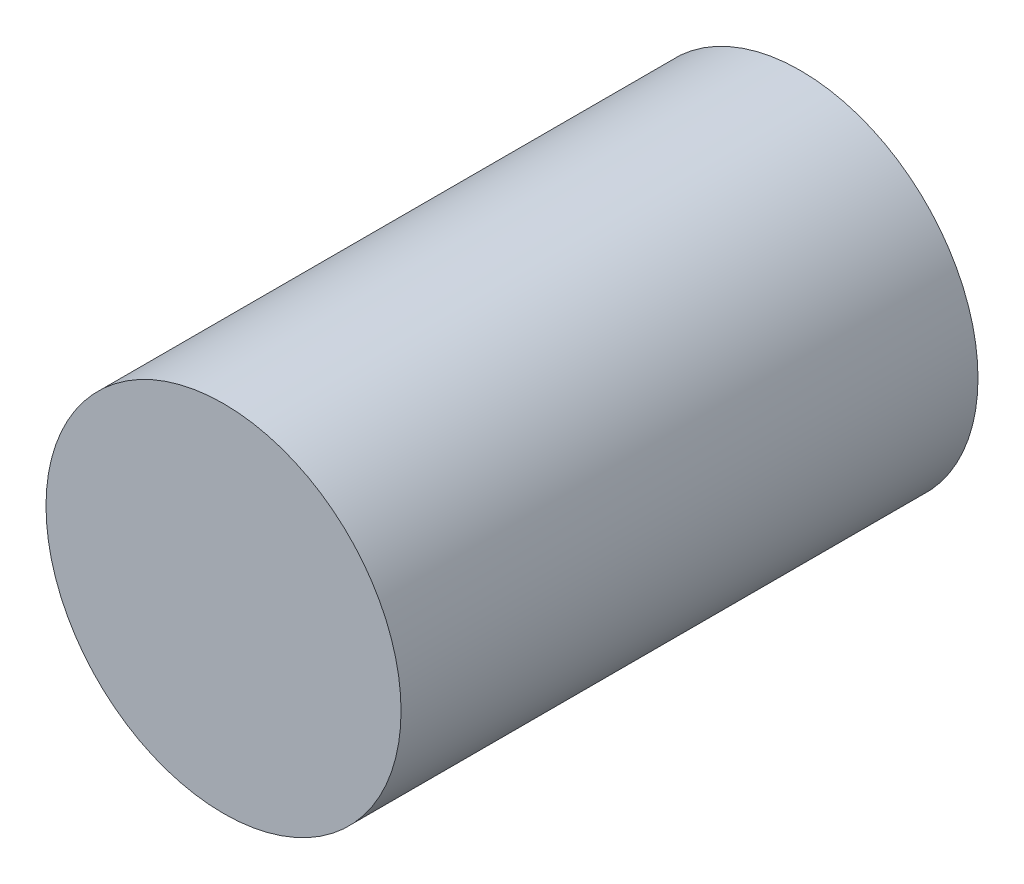
SolidWorks part; units mm, degrees
ref_plane "Front Plane" through (0, 0, 0) normal (0, 0, 1) x (1, 0, 0)
ref_plane "Top Plane" through (0, 0, 0) normal (0, 1, 0) x (1, 0, 0)
ref_plane "Right Plane" through (0, 0, 0) normal (1, 0, 0) x (0, 0, -1)
sketch "Sketch1" plane through (0, 0, 0) normal (0, 0, 1) x (1, 0, 0)
  circle A0 centre (4, 4) radius 4
  dimension "D1" = 8
extrude "Profile" add sketch "Sketch1" along normal blind 13
equation "\"Profile_Depth\"= 13mm"
equation "\"D1@Profile\" = \"Profile_Depth\""
equation "\"Profile_Sketch_1\"= 8mm"
equation "\"D1@Sketch1\" = \"Profile_Sketch_1\""
equation "\"EnvelopeWidth\"= 8mm"
equation "\"EnvelopeHeight\"= 8mm"
